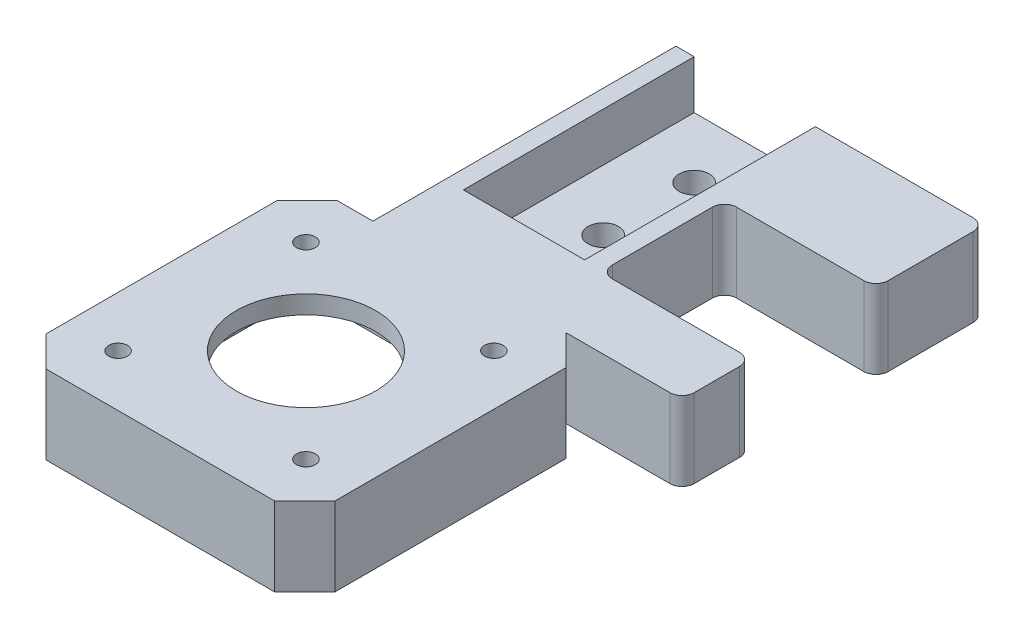
SolidWorks part; units mm, degrees
ref_plane "前视基准面" through (0, 0, 0) normal (0, 0, 1) x (1, 0, 0)
ref_plane "上视基准面" through (0, 0, 0) normal (0, 1, 0) x (1, 0, 0)
ref_plane "右视基准面" through (0, 0, 0) normal (1, 0, 0) x (0, 0, -1)
sketch "草图1" plane through (0, 0, 0) normal (0, 1, 0) x (1, 0, 0)
  line L8 (-16.1543, -20.9614) -> (15.8457, -20.9614)
  line L13 (15.8457, -20.9614) -> (20.8457, -15.9614)
  line L14 (20.8457, -15.9614) -> (20.8457, 16.0386)
  line L15 (20.8457, 16.0386) -> (15.8457, 21.0386)
  line L16 (15.8457, 21.0386) -> (-16.1543, 21.0386)
  line L17 (-16.1543, 21.0386) -> (-21.1543, 16.0386)
  line L18 (-21.1543, 16.0386) -> (-21.1543, -15.9614)
  line L19 (-21.1543, -15.9614) -> (-16.1543, -20.9614)
  line L21 (23.8457, 24.0386) -> (-23.8457, 24.0386)
  line L22 (23.8457, 24.0386) -> (23.8457, -24.0386)
  line L23 (23.8457, -24.0386) -> (-23.8457, -24.0386)
  line L24 (-23.8457, 24.0386) -> (-23.8457, -24.0386)
  line L25 (23.8457, 24.0386) -> (-23.8457, -24.0386) construction
  line L26 (23.8457, -24.0386) -> (-23.8457, 24.0386) construction
  circle A4 centre (-15.6543, -15.4614) radius 1.6
  circle A5 centre (15.3457, -15.4614) radius 1.6
  circle A6 centre (15.3457, 15.5386) radius 1.6
  circle A7 centre (-15.6543, 15.5386) radius 1.6
  point P16 (0, 0)
  dimension "D1" = 3
  dimension "D2" = 3
extrude "凸台-拉伸2" add sketch "草图1" along normal blind 10 contours L21 L24 L23 L22 L19 L18 L17 L16 L15 L14 L13 L8
sketch "草图4" plane through (0, 10, 0) normal (0, 1, 0) x (1, 0, 0)
  line L1 (-23.8457, 24.0386) -> (23.8457, 24.0386)
  line L2 (-23.8457, 24.0386) -> (-23.8457, -24.0386)
  line L3 (-23.8457, -24.0386) -> (23.8457, -24.0386)
  line L4 (23.8457, 24.0386) -> (23.8457, -24.0386)
extrude "凸台-拉伸3" add sketch "草图4" along normal blind 3
sketch "草图5" plane through (0, 10, 0) normal (0, -1, 0) x (1, 0, 0)
  line L0 (33.7944, -17.0416) -> (65.7944, -17.0416)
  line L1 (65.7944, -17.0416) -> (70.7944, -12.0416)
  line L2 (70.7944, -12.0416) -> (70.7944, 19.9584)
  line L3 (70.7944, 19.9584) -> (65.7944, 24.9584)
  line L4 (65.7944, 24.9584) -> (33.7944, 24.9584)
  line L5 (33.7944, 24.9584) -> (28.7944, 19.9584)
  line L6 (28.7944, 19.9584) -> (28.7944, -12.0416)
  line L7 (28.7944, -12.0416) -> (33.7944, -17.0416)
  line L9 (15.5, 15.5) -> (-15.5, 15.5)
  line L10 (15.5, 15.5) -> (15.5, -15.5)
  line L11 (15.5, -15.5) -> (-15.5, -15.5)
  line L12 (-15.5, 15.5) -> (-15.5, -15.5)
  line L13 (15.5, 15.5) -> (-15.5, -15.5) construction
  line L14 (15.5, -15.5) -> (-15.5, 15.5) construction
  circle A0 centre (34.2944, -11.5416) radius 1.6
  circle A1 centre (65.2944, -11.5416) radius 1.6
  circle A2 centre (65.2944, 19.4584) radius 1.6
  circle A3 centre (34.2944, 19.4584) radius 1.6
  circle A4 centre (-15.5, 15.5) radius 1.55
  circle A5 centre (15.5, 15.5) radius 1.55
  circle A6 centre (15.5, -15.5) radius 1.55
  circle A7 centre (-15.5, -15.5) radius 1.55
  point P16 (0, 0)
  point P32 (0, 0)
  dimension "D1" = 31
  dimension "D4" = 3.1
  dimension "D2" = 31
  dimension "D3" = 31
  dimension "D5" = 4
extrude "切除-拉伸1" cut sketch "草图5" against normal blind 3 contours L12 A7 L11 | L11 A7 L12 | L10 A6 L11 | L11 A6 L10 | L10 A5 L9 | L9 A5 L10 | L9 A4 L12 | L12 A4 L9
sketch "草图6" plane through (0, 13, 0) normal (0, 1, 0) x (1, 0, 0)
  circle A0 centre (0, 0) radius 11.5
  dimension "D1" = 23
extrude "切除-拉伸2" cut sketch "草图6" against normal blind 3
chamfer "倒角1" distance 5 angle 45 4 edges at (-23.8457, 6.5, 24.0386) (23.8457, 6.5, 24.0386) (23.8457, 6.5, -24.0386) (-23.8457, 6.5, -24.0386)
sketch "草图7" plane through (0, 0, -24.0386) normal (0, 0, -1) x (-1, 0, 0)
  line L0 (-18.8457, 13) -> (18.8457, 13) construction
  line L1 (-13, 13) -> (13, 13)
  line L2 (-13, 13) -> (-13, 0)
  line L3 (-13, 0) -> (13, 0)
  line L4 (13, 13) -> (13, 0)
  line L5 (-18.8457, 0) -> (18.8457, 0) construction
  dimension "D1" = 26
  dimension "D2" = 13
extrude "凸台-拉伸4" add sketch "草图7" along normal blind 50
sketch "草图8" plane through (0, 13, 0) normal (0, 1, 0) x (1, 0, 0)
  line L0 (-13, 74.0386) -> (13, 74.0386) construction
  line L1 (-10, 74.0386) -> (10, 74.0386)
  line L2 (-10, 74.0386) -> (-10, 34.0386)
  line L3 (-10, 34.0386) -> (10, 34.0386)
  line L4 (10, 74.0386) -> (10, 34.0386)
  line L5 (13, 74.0386) -> (13, 24.0386) construction
  line L6 (-13, 74.0386) -> (-13, 24.0386) construction
  dimension "D1" = 3
  dimension "D2" = 3
  dimension "D3" = 40
extrude "切除-拉伸3" cut sketch "草图8" against normal blind 8
sketch "草图9" plane through (0, 0, -34.0386) normal (0, 0, -1) x (-1, 0, 0)
  line L4 (10, 13) -> (-10, 13)
  line L5 (-10, 13) -> (-10, 5)
  line L6 (-10, 5) -> (10, 5)
  line L7 (10, 5) -> (10, 13)
  line L8 (10, 13) -> (-10, 13)
  line L9 (-10, 13) -> (-10, 5)
  line L10 (-10, 5) -> (10, 5)
  line L11 (10, 5) -> (10, 13)
  dimension "D1" = 0
extrude "凸台-拉伸5" add sketch "草图9" along normal blind 1.93
sketch "草图10" plane through (13, 0, 0) normal (1, 0, 0) x (0, 0, -1)
  line L0 (74.0386, 0) -> (24.0386, 0) construction
  line L1 (24.0386, 13) -> (35.5386, 13)
  line L2 (24.0386, 13) -> (24.0386, 0)
  line L3 (24.0386, 0) -> (35.5386, 0)
  line L4 (35.5386, 13) -> (35.5386, 0)
  line L5 (74.0386, 13) -> (24.0386, 13) construction
  line L6 (56.0386, 13) -> (74.0386, 13)
  line L7 (56.0386, 13) -> (56.0386, 0)
  line L8 (56.0386, 0) -> (74.0386, 0)
  line L9 (74.0386, 13) -> (74.0386, 0)
  dimension "D1" = 11.5
  dimension "D2" = 18
extrude "凸台-拉伸6" add sketch "草图10" along normal blind 25
fillet "圆角1" radius 2 7 edges at (38, 6.5, -24.0386) (38, 6.5, -35.5386) (38, 6.5, -74.0386) (38, 6.5, -56.0386) (-13, 0, -49.0386) (13, 6.5, -35.5386) (13, 6.5, -56.0386)
sketch "草图11" plane through (0, 5, 0) normal (0, 1, 0) x (1, 0, 0)
  line L0 (0, 74.0386) -> (0, 35.9686) construction
  line L1 (10, 74.0386) -> (-10, 74.0386) construction
  line L2 (10, 35.9686) -> (-10, 35.9686) construction
  circle A0 centre (0, 64.0386) radius 2.5
  circle A1 centre (0, 49.0386) radius 2.5
  dimension "D1" = 5
  dimension "D2" = 5
  dimension "D3" = 15
  dimension "D4" = 10
extrude "切除-拉伸4" cut sketch "草图11" against normal blind 25
